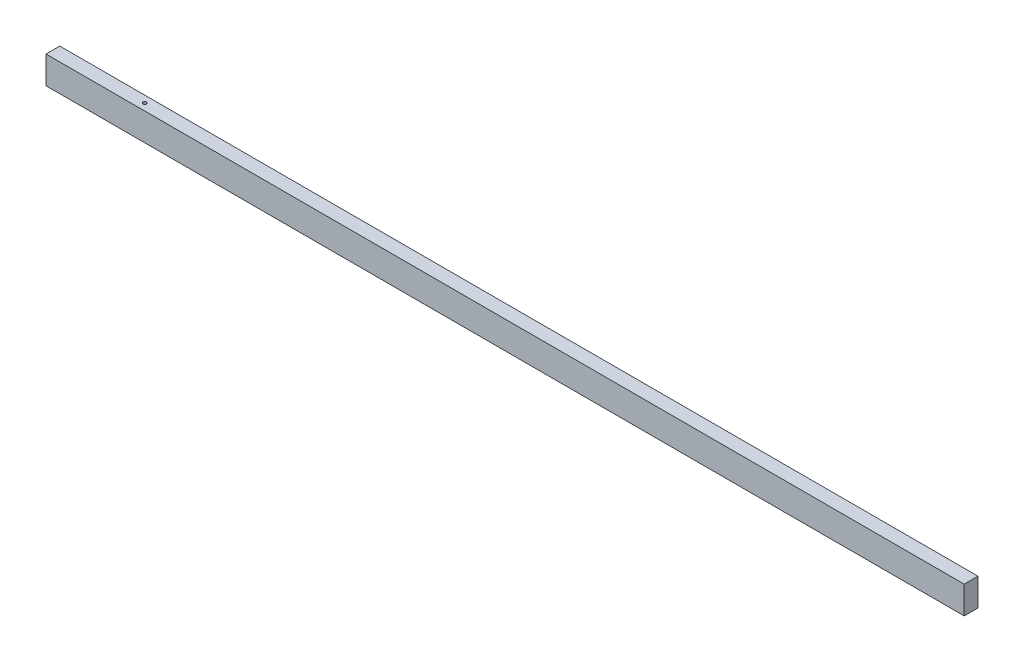
SolidWorks part; units mm, degrees
material "Pine"
ref_plane "Piano frontale" through (0, 0, 0) normal (0, 0, 1) x (1, 0, 0)
ref_plane "Piano superiore" through (0, 0, 0) normal (0, 1, 0) x (1, 0, 0)
ref_plane "Piano destro" through (0, 0, 0) normal (1, 0, 0) x (0, 0, -1)
sketch "Sketch1" plane through (0, 0, 0) normal (0, 0, 1) x (1, 0, 0)
  line L1 (0, 0) -> (100, 0)
  line L2 (0, 0) -> (0, 3)
  line L3 (0, 3) -> (100, 3)
  line L4 (100, 0) -> (100, 3)
  dimension "D1" = 3
  dimension "D2" = 100
extrude "Boss-Extrude1" add sketch "Sketch1" along normal blind 1.5
scale "Scale1" scale about origin uniform scaling yes scale factor 10
hole_wizard "#6 (0.204) Diameter Hole1" positions "Sketch6" profile "Sketch7" hole size "#6" standard "ANSI Inch"
sketch "Sketch6" plane through (-109.4185, 30, -1000) normal (0, 1, 0) x (1, 0, 0)
  point P0 (209.4185, -1007.5)
sketch "Sketch7" plane through (100, 30, 7.5) normal (1, 0, 0) x (0, 0, 1)
  line L0 (0, 0) -> (0, 49)
  line L1 (0, 49) -> (1.905, 49)
  line L2 (1.905, 49) -> (1.905, 0)
  line L3 (1.905, 0) -> (0, 0)
  line L4 (0, -6.35) -> (0, 107.95) construction
  dimension "Thru Hole Dia." = 3.81
  dimension "Thru Hole Depth" = 49
